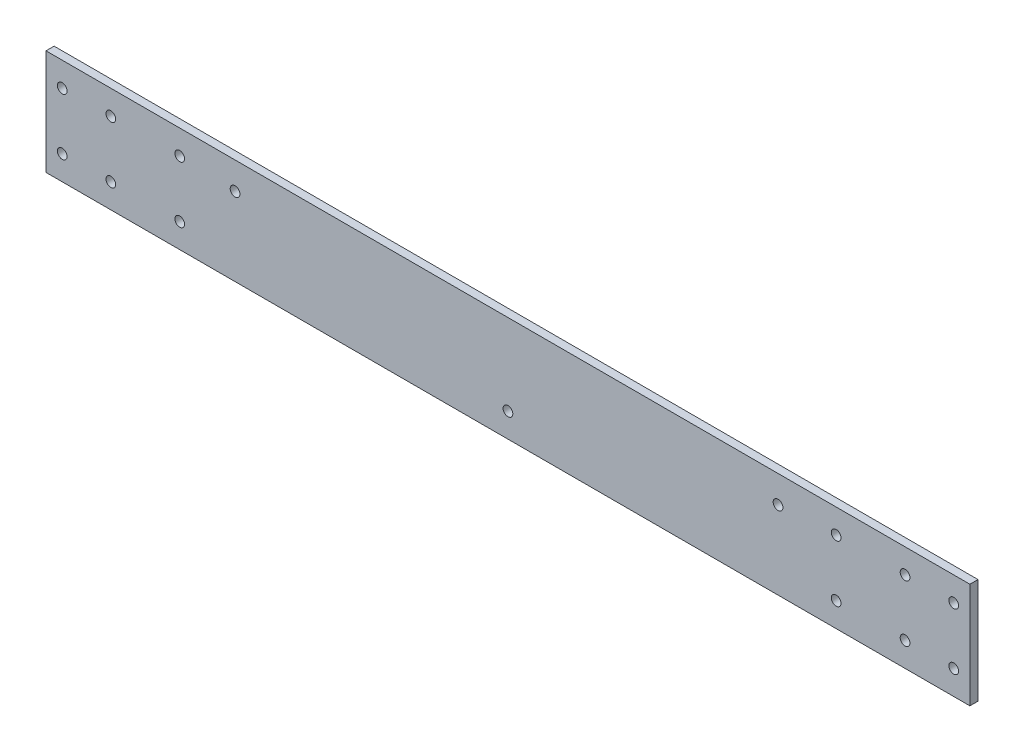
SolidWorks part; units mm, degrees
ref_plane "前视基准面" through (0, 0, 0) normal (0, 0, 1) x (1, 0, 0)
ref_plane "上视基准面" through (0, 0, 0) normal (0, 1, 0) x (1, 0, 0)
ref_plane "右视基准面" through (0, 0, 0) normal (1, 0, 0) x (0, 0, -1)
sketch "草图1" plane through (0, 0, 0) normal (0, 0, 1) x (1, 0, 0)
  line L0 (0, 78.8621) -> (0, -78.8621) construction
  line L1 (-446.7703, 0) -> (446.7703, 0) construction
  line L2 (-570, 35) -> (570, 35) construction
  line L3 (-570, 65) -> (570, 65)
  line L4 (-570, 65) -> (-570, -65)
  line L5 (-570, -65) -> (570, -65)
  line L6 (570, 65) -> (570, -65)
  line L7 (-570, -35) -> (570, -35) construction
  line L8 (-550, 65) -> (-550, -65) construction
  line L9 (-490, 65) -> (-490, -65) construction
  line L10 (-405, 65) -> (-405, -65) construction
  line L11 (405, 65) -> (405, -65) construction
  line L12 (490, 65) -> (490, -65) construction
  line L13 (550, 65) -> (550, -65) construction
  circle A0 centre (-550, 35) radius 6
  circle A1 centre (-490, 35) radius 6
  circle A2 centre (-405, 35) radius 6
  circle A3 centre (-550, -35) radius 6
  circle A4 centre (-490, -35) radius 6
  circle A5 centre (-405, -35) radius 6
  circle A6 centre (405, -35) radius 6
  circle A7 centre (490, -35) radius 6
  circle A8 centre (550, -35) radius 6
  circle A9 centre (405, 35) radius 6
  circle A10 centre (490, 35) radius 6
  circle A11 centre (550, 35) radius 6
  dimension "D5" = 12
  dimension "D6" = 810
  dimension "D1" = 1140
  dimension "D2" = 130
  dimension "D3" = 30
  dimension "D4" = 70
  dimension "D7" = 980
  dimension "D8" = 1100
extrude "凸台-拉伸1" add sketch "草图1" along normal blind 10
sketch "草图2" plane through (0, 0, 10) normal (0, 0, 1) x (1, 0, 0)
  circle A0 centre (0, -35) radius 6
extrude "切除-拉伸1" cut sketch "草图2" against normal through all
sketch "草图3" plane through (0, 0, 10) normal (0, 0, 1) x (1, 0, 0)
  circle A0 centre (333.278, 31.4673) radius 6
extrude "切除-拉伸2" cut sketch "草图3" against normal through all
sketch "草图4" plane through (0, 0, 10) normal (0, 0, 1) x (1, 0, 0)
  circle A0 centre (-336.722, 31.4673) radius 6
extrude "切除-拉伸3" cut sketch "草图4" against normal through all
